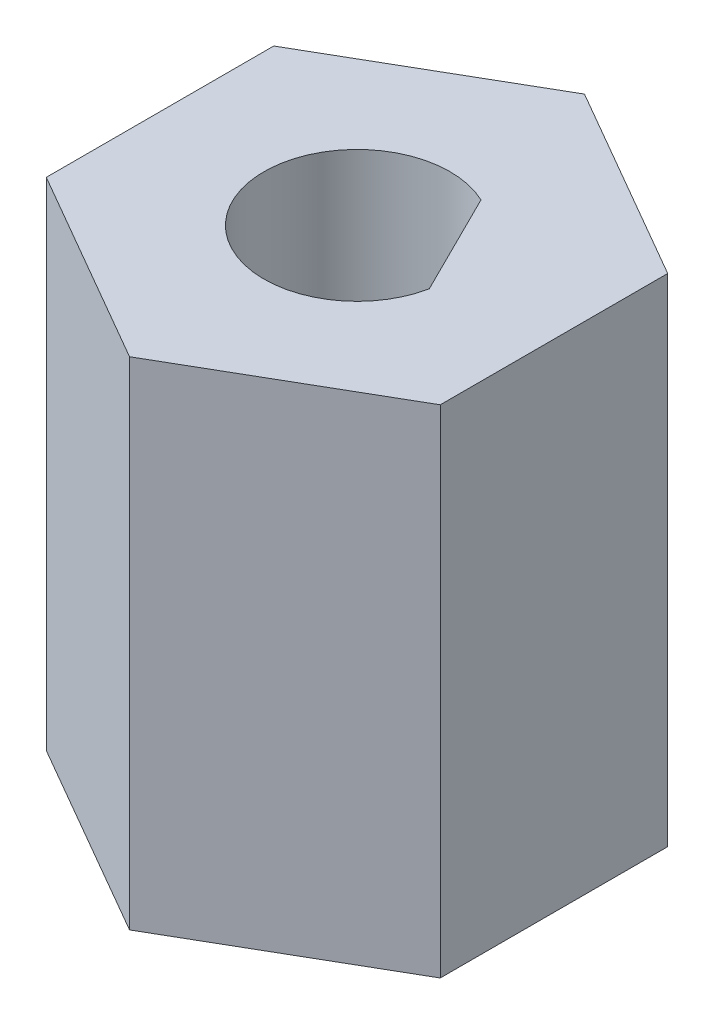
SolidWorks part; units mm, degrees
ref_plane "Front" through (0, 0, 0) normal (0, 0, 1) x (1, 0, 0)
ref_plane "Top" through (0, 0, 0) normal (0, 1, 0) x (1, 0, 0)
ref_plane "Right" through (0, 0, 0) normal (1, 0, 0) x (0, 0, -1)
sketch "Sketch1" plane through (0, 0, 0) normal (0, 1, 0) x (1, 0, 0)
  line L1 (0, -7.3323) -> (6.35, -3.6662)
  line L2 (6.35, -3.6662) -> (6.35, 3.6662)
  line L3 (6.35, 3.6662) -> (0, 7.3323)
  line L4 (0, 7.3323) -> (-6.35, 3.6662)
  line L5 (-6.35, 3.6662) -> (-6.35, -3.6662)
  line L6 (-6.35, -3.6662) -> (0, -7.3323)
  circle A0 centre (0, 0) radius 6.35 construction
  dimension "D1" = 12.7
extrude "Boss-Extrude1" add sketch "Sketch1" along normal blind 16.002
sketch "Sketch2" plane through (0, 16.002, 0) normal (0, 1, 0) x (1, 0, 0)
  line L0 (2.9374, -0.6097) -> (1.2862, 2.7103)
  circle A0 centre (0, 0) radius 3
  dimension "D1" = 3.32
extrude "Cut-Extrude1" cut sketch "Sketch2" against normal blind 30 and the other way blind 3.175 contours L0 A0
